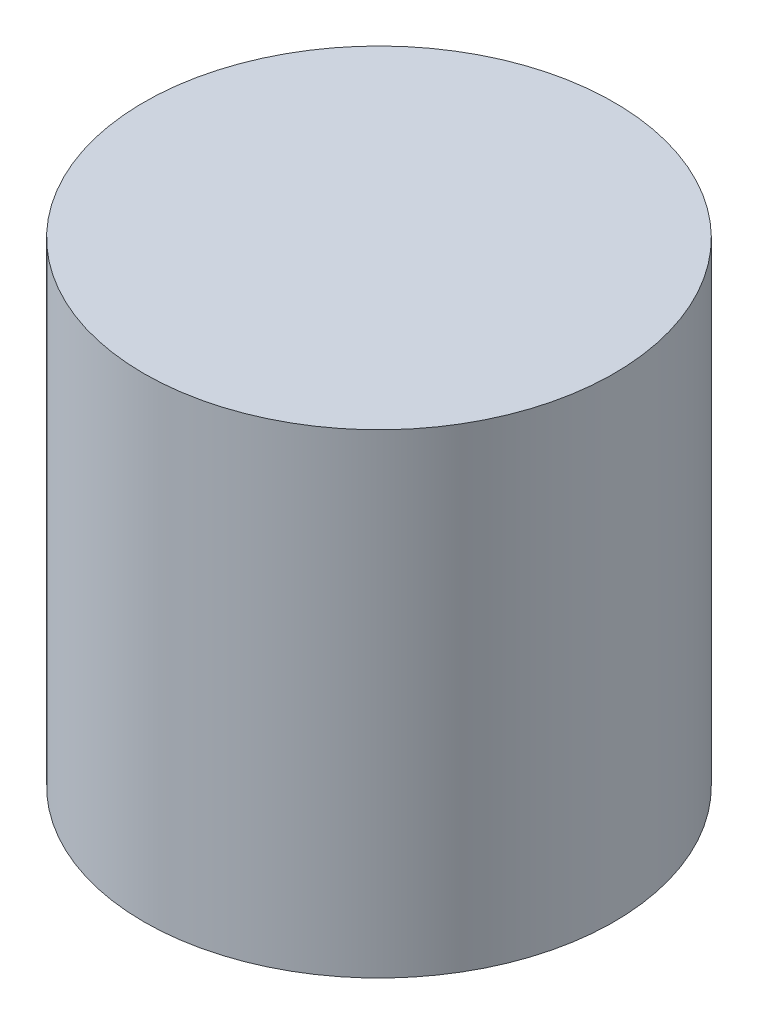
SolidWorks part; units mm, degrees
ref_plane "Front Plane" through (0, 0, 0) normal (0, 0, 1) x (1, 0, 0)
ref_plane "Top Plane" through (0, 0, 0) normal (0, 1, 0) x (1, 0, 0)
ref_plane "Right Plane" through (0, 0, 0) normal (1, 0, 0) x (0, 0, -1)
sketch "Sketch1" plane through (0, 0, 0) normal (0, 1, 0) x (1, 0, 0)
  circle A0 centre (0, 0) radius 9.9
  dimension "D1" = 19.8
extrude "Boss-Extrude1" add sketch "Sketch1" along normal blind 20
